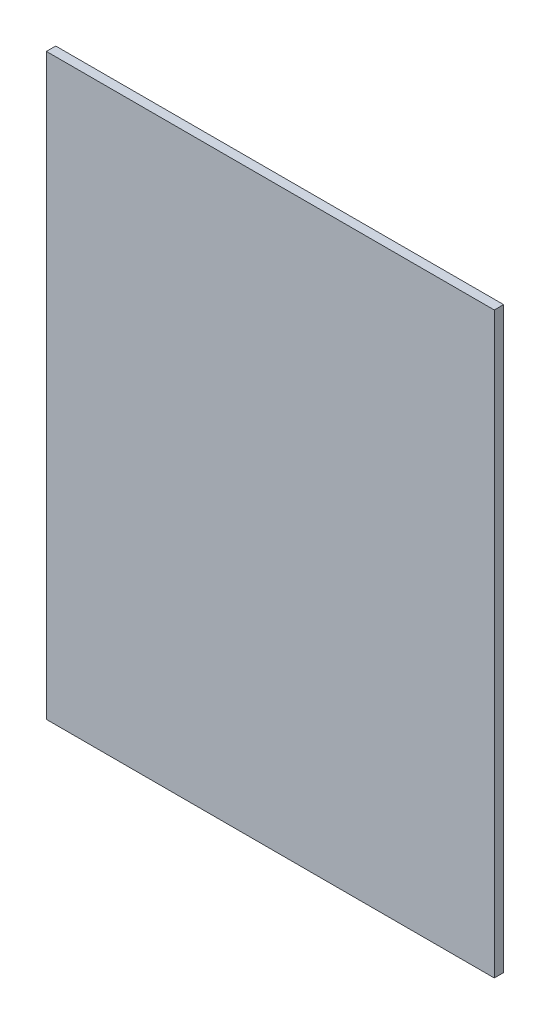
SolidWorks part; units mm, degrees
ref_plane "Plan de face" through (0, 0, 0) normal (0, 0, 1) x (1, 0, 0)
ref_plane "Plan de dessus" through (0, 0, 0) normal (0, 1, 0) x (1, 0, 0)
ref_plane "Plan de droite" through (0, 0, 0) normal (1, 0, 0) x (0, 0, -1)
sketch "Esquisse1" plane through (0, 0, 0) normal (0, 0, 1) x (1, 0, 0)
  line L1 (-120, -155) -> (120, -155)
  line L2 (-120, -155) -> (-120, 155)
  line L3 (-120, 155) -> (120, 155)
  line L4 (120, -155) -> (120, 155)
  line L5 (-120, -155) -> (120, 155) construction
  line L6 (-120, 155) -> (120, -155) construction
  point P0 (0, 0)
  dimension "D1" = 310
  dimension "D2" = 240
extrude "Boss.-Extru.1" add sketch "Esquisse1" along normal blind 5
